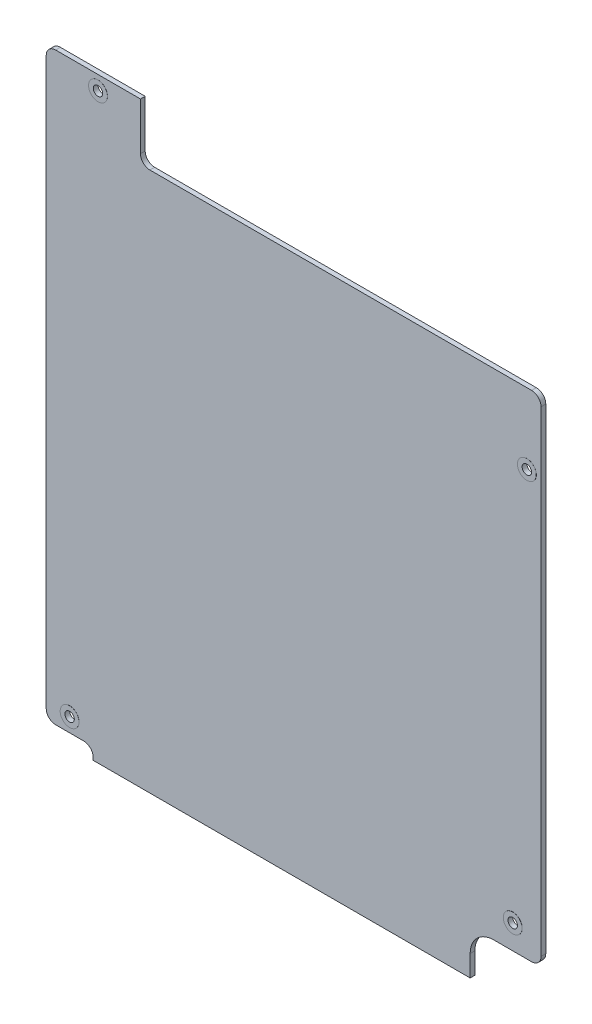
SolidWorks part; units mm, degrees
ref_plane "Front Plane" through (0, 0, 0) normal (0, 0, 1) x (1, 0, 0)
ref_plane "Top Plane" through (0, 0, 0) normal (0, 1, 0) x (1, 0, 0)
ref_plane "Right Plane" through (0, 0, 0) normal (1, 0, 0) x (0, 0, -1)
sketch "Sketch1" plane through (0, 0, 0) normal (0, 0, 1) x (1, 0, 0)
  line L0 (-52.5, 52.5) -> (-52.5, 64.5521) construction
  line L1 (-30.5, 52.5) -> (50.5, 52.5)
  line L2 (-52.5, 52.5) -> (-52.5, -52.5)
  line L4 (52.5, 50.5) -> (52.5, -50.5)
  line L7 (52.5, -52.5) -> (52.5, -62) construction
  line L12 (52.5, -62) -> (37.4563, -62) construction
  line L13 (42.4563, -52.5) -> (50.5, -52.5)
  line L14 (-50.5, 64.5521) -> (-32.5, 64.5521)
  line L15 (-52.5, 62.5521) -> (-52.5, -57.4479)
  line L16 (-50.5, -59.4479) -> (-44.5437, -59.4479)
  line L17 (-32.5, 64.5521) -> (-32.5, 54.5)
  line L18 (37.4563, -62) -> (-42.5437, -62)
  line L19 (37.4563, -62) -> (37.4563, -57.5)
  line L21 (-42.5437, -62) -> (-42.5437, -61.4479)
  arc A0 (37.4563, -57.5) -> (42.4563, -52.5) centre (42.4563, -57.5) cw
  arc A1 (-42.5437, -61.4479) -> (-44.5437, -59.4479) centre (-44.5437, -61.4479) ccw
  arc A2 (-30.5, 52.5) -> (-32.5, 54.5) centre (-30.5, 54.5) cw
  arc A3 (52.5, 50.5) -> (50.5, 52.5) centre (50.5, 50.5) ccw
  arc A4 (52.5, -50.5) -> (50.5, -52.5) centre (50.5, -50.5) cw
  arc A5 (-50.5, -59.4479) -> (-52.5, -57.4479) centre (-50.5, -57.4479) cw
  arc A6 (-52.5, 62.5521) -> (-50.5, 64.5521) centre (-50.5, 62.5521) cw
  point P0 (0, 0)
  point P23 (52.5, 52.5)
  dimension "D3" = 5
  dimension "D4" = 2
  dimension "D5" = 2
  dimension "D6" = 2
  dimension "D1" = 105
  dimension "D2" = 105
extrude "Boss-Extrude1" add sketch "Sketch1" along normal blind 1 contours A6 L15 L2 A5 L16 A1 L21 L18 L19 A0 L13 A4 L4 A3 L1 A2 L17 L14
sketch "Sketch2" plane through (0, 0, 1) normal (0, 0, 1) x (1, 0, 0)
  line L0 (-41.5, 64.5521) -> (-41.5, 61.5521) construction
  line L1 (-50.5, 64.5521) -> (-32.5, 64.5521) construction
  line L2 (-47.5219, -59.4479) -> (-47.5219, -56.4479) construction
  line L3 (-50.5, -59.4479) -> (-44.5437, -59.4479) construction
  line L4 (52.5, 37.4742) -> (49.5, 37.4742) construction
  line L5 (52.5, 50.5) -> (52.5, -50.5) construction
  line L6 (52.5, -47.3402) -> (46.5, -47.3402) construction
  circle A0 centre (-41.5, 61.5521) radius 1
  circle A1 centre (-47.5219, -56.4479) radius 1
  circle A2 centre (49.5, 37.4742) radius 1
  circle A3 centre (46.5, -47.3402) radius 1
extrude "Cut-Extrude1" cut sketch "Sketch2" against normal blind 10
sketch "Sketch3" plane through (0, 0, 1) normal (0, 0, 1) x (1, 0, 0)
  circle A0 centre (-47.5219, -56.4479) radius 2
  circle A1 centre (-41.5, 61.5521) radius 2
  circle A2 centre (49.5, 37.4742) radius 2
  circle A3 centre (46.5, -47.3402) radius 2
extrude "Extrude-Thin1" add sketch "Sketch3" along normal blind 0.02 thin thin type one direction reverse wall 1
